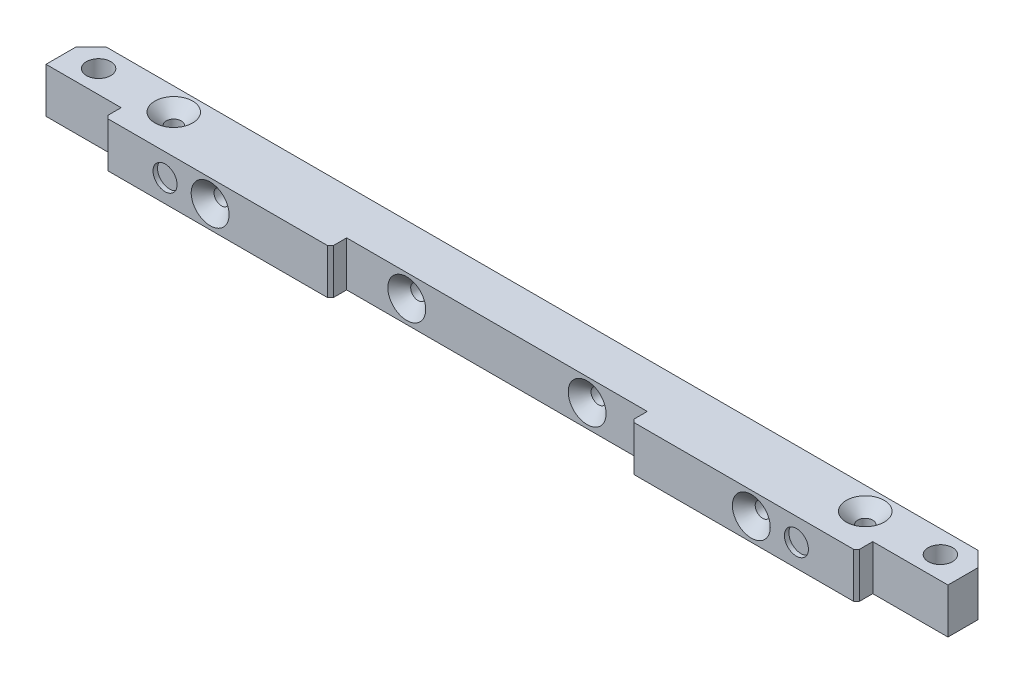
SolidWorks part; units mm, degrees
material "3.1355 (EN-AW 2024)"
ref_plane "Front" through (0, 0, 0) normal (0, 0, 1) x (1, 0, 0)
ref_plane "Top" through (0, 0, 0) normal (0, 1, 0) x (1, 0, 0)
ref_plane "Right" through (0, 0, 0) normal (1, 0, 0) x (0, 0, -1)
sketch "Эскиз1" plane through (0, 0, 0) normal (0, 1, 0) x (1, 0, 0)
  line L1 (-150, 7.5) -> (150, 7.5)
  line L2 (-150, 7.5) -> (-150, -7.5)
  line L3 (-150, -7.5) -> (150, -7.5)
  line L4 (150, 7.5) -> (150, -7.5)
  line L5 (-150, 7.5) -> (150, -7.5) construction
  line L6 (-150, -7.5) -> (150, 7.5) construction
  point P0 (0, 0)
  dimension "D1" = 300
  dimension "D2" = 15
extrude "База" add sketch "Эскиз1" along normal blind 15
hole_wizard "Крепление шарнира M6" positions "Эскиз2" profile "Эскиз3" tap size "M6" standard "DIN" end condition through all
sketch "Эскиз2" plane through (0, 15, 0) normal (0, 1, 0) x (1, 0, 0)
  line L6 (-115, 0) -> (0, 0) construction
  line L7 (0, 0) -> (115, 0) construction
  point P3 (-115, 0)
  point P5 (115, 0)
  dimension "D1" = 230
sketch "Эскиз3" plane through (-115, 15, 0) normal (1, 0, 0) x (0, 0, 1)
  line L0 (0, 0) -> (0, 15)
  line L1 (0, 15) -> (2.5, 15)
  line L2 (2.5, 15) -> (2.5, 3.8)
  line L3 (2.5, 3.8) -> (6.3, 0)
  line L5 (6.3, 0) -> (0, 0)
  line L6 (-2.5, 3.8) -> (-6.3, 0) construction
  line L11 (0, -6.35) -> (0, 107.95) construction
  dimension "Диаметр проходного сверла" = 5
  dimension "Глубина проходного сверла" = 15
  dimension "Диаметр передней зенковки" = 12.6
  dimension "Угол передней зенковки" = 90
cosmetic thread "Отверстие резьбы12" parameters "D2"=6
cosmetic thread "Отверстие резьбы13" parameters "D2"=6
hole_wizard "Отверстие-8.1мм" positions "Эскиз6" profile "Эскиз7" hole size "Ø8.0" standard "DIN" end condition through all
sketch "Эскиз6" plane through (0, 15, 0) normal (0, 1, 0) x (1, 0, 0)
  line L2 (-140, 0) -> (-150, 0) construction
  line L3 (-150, 7.5) -> (-150, -7.5) construction
  line L8 (140, 0) -> (150, 0) construction
  line L9 (150, -7.5) -> (150, 7.5) construction
  point P0 (-140, 0)
  point P2 (140, 0)
  dimension "D1" = 10
sketch "Эскиз7" plane through (-140, 15, 0) normal (1, 0, 0) x (0, 0, 1)
  line L0 (0, 0) -> (0, 15)
  line L1 (0, 15) -> (4.05, 15)
  line L2 (4.05, 15) -> (4.05, 0)
  line L5 (4.05, 0) -> (0, 0)
  line L11 (0, -6.35) -> (0, 107.95) construction
  dimension "Диаметр сквозного отверстия" = 8.1
  dimension "Глубина сквозного отверстия" = 15
sketch "Эскиз8" plane through (0, 0, 7.5) normal (0, 0, 1) x (1, 0, 0)
  line L0 (-150, 15) -> (150, 15) construction
  line L1 (-125, 15) -> (125, 15)
  line L2 (-125, 15) -> (-125, 0)
  line L3 (-125, 0) -> (125, 0)
  line L4 (125, 15) -> (125, 0)
  line L5 (-150, 0) -> (150, 0) construction
  point P8 (0, 0)
  dimension "D1" = 250
extrude "Направляющая" add sketch "Эскиз8" along normal blind 5.4
sketch "Эскиз9" plane through (0, 0, 12.9) normal (0, 0, 1) x (1, 0, 0)
  line L0 (0, 7.5) -> (0, 15) construction
  line L1 (125, 15) -> (-125, 15) construction
  line L2 (0, 7.5) -> (0, 0) construction
  line L5 (-105, 7.5) -> (105, 7.5) construction
  circle A1 centre (-105, 7.5) radius 4
  circle A2 centre (105, 7.5) radius 4
  point P1 (0, 7.5)
  dimension "D1" = 8
  dimension "D2" = 210
extrude "Магниты" cut sketch "Эскиз9" against normal blind 1.5
sketch "Эскиз10" plane through (0, 0, 12.9) normal (0, 0, 1) x (1, 0, 0)
  line L0 (125, 15) -> (-125, 15) construction
  line L1 (-50, 15) -> (50, 15)
  line L2 (-50, 15) -> (-50, 0)
  line L3 (-50, 0) -> (50, 0)
  line L4 (50, 15) -> (50, 0)
  line L5 (-125, 0) -> (125, 0) construction
  point P8 (0, 15)
  dimension "D1" = 100
extrude "Вырез" cut sketch "Эскиз10" against normal blind 5.4
hole_wizard "Прижим-1-M6" positions "Эскиз4" profile "Эскиз5" tap size "M6" standard "DIN" end condition through all
sketch "Эскиз4" plane through (0, 0, 12.9) normal (0, 0, 1) x (1, 0, 0)
  line L23 (90, 7.5) -> (30, 7.5) construction
  line L24 (30, 7.5) -> (-30, 7.5) construction
  line L25 (-30, 7.5) -> (-90, 7.5) construction
  line L26 (0, 7.5) -> (0, 15) construction
  line L27 (150, 15) -> (-150, 15) construction
  line L30 (0, 7.5) -> (0, 0) construction
  point P4 (-90, 7.5)
  point P8 (90, 7.5)
  point P65 (0, 7.5)
  dimension "D1" = 180
sketch "Эскиз5" plane through (-90, 7.5, 12.9) normal (1, 0, 0) x (0, -1, 0)
  line L0 (0, 0) -> (0, 20.4)
  line L1 (0, 20.4) -> (2.5, 20.4)
  line L2 (2.5, 20.4) -> (2.5, 3.8)
  line L3 (2.5, 3.8) -> (6.3, 0)
  line L5 (6.3, 0) -> (0, 0)
  line L6 (-2.5, 3.8) -> (-6.3, 0) construction
  line L11 (0, -6.35) -> (0, 107.95) construction
  dimension "Диаметр проходного сверла" = 5
  dimension "Глубина проходного сверла" = 20.4
  dimension "Диаметр передней зенковки" = 12.6
  dimension "Угол передней зенковки" = 90
cosmetic thread "Отверстие резьбы16" parameters "D2"=6
cosmetic thread "Отверстие резьбы17" parameters "D2"=6
hole_wizard "Прижим-2-M6" positions "Эскиз11" profile "Эскиз12" tap size "M6" standard "ISO" end condition through all
sketch "Эскиз11" plane through (0, 0, 7.5) normal (0, 0, 1) x (1, 0, 0)
  line L0 (-30, 7.5) -> (0, 7.5) construction
  line L1 (0, 7.5) -> (30, 7.5) construction
  line L4 (0, 7.5) -> (0, 15) construction
  line L5 (50, 15) -> (-50, 15) construction
  line L8 (0, 7.5) -> (0, 0) construction
  point P0 (-30, 7.5)
  point P2 (30, 7.5)
  dimension "D1" = 60
sketch "Эскиз12" plane through (-30, 7.5, 7.5) normal (1, 0, 0) x (0, -1, 0)
  line L0 (0, 0) -> (0, 15)
  line L1 (0, 15) -> (2.5, 15)
  line L2 (2.5, 15) -> (2.5, 3.8)
  line L3 (2.5, 3.8) -> (6.3, 0)
  line L5 (6.3, 0) -> (0, 0)
  line L6 (-2.5, 3.8) -> (-6.3, 0) construction
  line L11 (0, -6.35) -> (0, 107.95) construction
  dimension "Диаметр проходного сверла" = 5
  dimension "Глубина проходного сверла" = 15
  dimension "Диаметр передней зенковки" = 12.6
  dimension "Угол передней зенковки" = 90
cosmetic thread "Отверстие резьбы20" parameters "D1"=0, "D2"=6
cosmetic thread "Отверстие резьбы21" parameters "D1"=0, "D2"=6
chamfer "Фаска1" distance 5 angle 45 2 edges at (150, 7.5, -7.5) (-150, 7.5, -7.5)
chamfer "Фаска2" distance 1 angle 45 4 edges at (125, 7.5, 12.9) (50, 7.5, 12.9) (-50, 7.5, 12.9) (-125, 7.5, 12.9)
